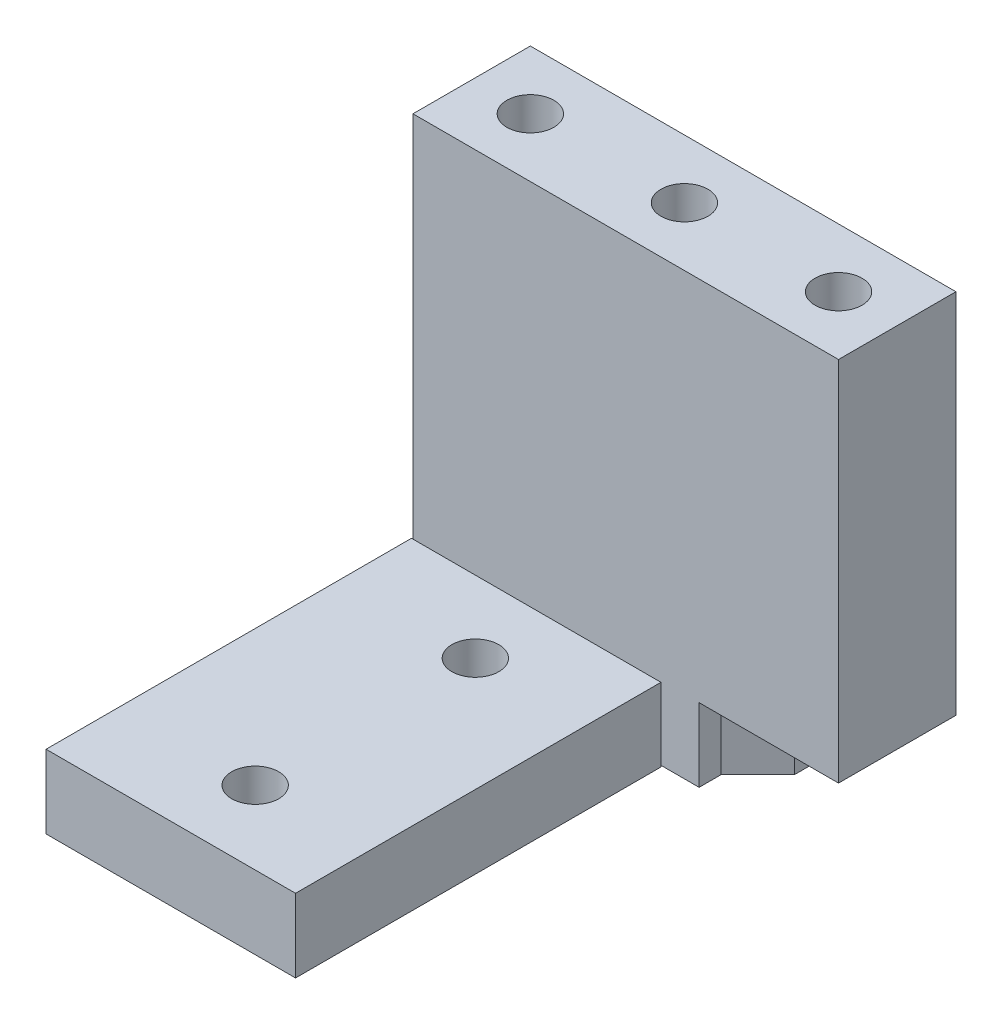
SolidWorks part; units mm, degrees
material "PLA"
ref_plane "前视基准面" through (0, 0, 0) normal (0, 0, 1) x (1, 0, 0)
ref_plane "上视基准面" through (0, 0, 0) normal (0, 1, 0) x (1, 0, 0)
ref_plane "右视基准面" through (0, 0, 0) normal (1, 0, 0) x (0, 0, -1)
sketch "草图2" plane through (0, 0, 0) normal (0, 0, 1) x (1, 0, 0)
  line L0 (-14.5, 15) -> (14.5, 15)
  line L1 (7.75, -7.75) -> (-7.75, -7.75) construction
  line L2 (7.75, -7.75) -> (7.75, 7.75) construction
  line L3 (7.75, 7.75) -> (-7.75, 7.75) construction
  line L4 (-7.75, -7.75) -> (-7.75, 7.75) construction
  line L5 (7.75, -7.75) -> (-7.75, 7.75) construction
  line L6 (7.75, 7.75) -> (-7.75, -7.75) construction
  line L7 (14.5, 15) -> (14.5, -10)
  line L9 (-14.5, -10) -> (-14.5, 15)
  line L10 (0, 0) -> (-11.4797, 0) construction
  line L11 (-7.05, -10.31) -> (-7.05, -9.46)
  line L12 (3.75, -3.69) -> (-7.05, -3.69)
  line L13 (3.75, -3.69) -> (3.75, -10.31)
  line L14 (3.75, -10.31) -> (-7.05, -10.31)
  line L15 (-7.05, -3.69) -> (-7.05, -10.31) construction
  line L16 (3.75, -3.69) -> (-7.05, -10.31) construction
  line L17 (3.75, -10.31) -> (-7.05, -3.69) construction
  line L18 (-7.05, -9.46) -> (2.9, -9.46)
  line L19 (2.9, -9.46) -> (2.9, -4.54)
  line L20 (2.9, -4.54) -> (-7.05, -4.54)
  line L21 (-7.05, -4.54) -> (-7.05, -3.69)
  line L22 (14.5, -10) -> (7.5, -10)
  line L23 (7.5, -10) -> (7.5, -15)
  line L24 (7.5, -15) -> (-14.5, -15)
  line L25 (-14.5, -15) -> (-14.5, -10)
  circle A0 centre (3.25, -10.31) radius 0.5
  circle A1 centre (3.25, -3.69) radius 0.5
  point P0 (0, 0)
  point P9 (-1.65, -7)
  point P28 (7.5, -12.5)
  dimension "D2" = 10.8
  dimension "D13" = 1
  dimension "D1" = 15.5
  dimension "D3" = 6.75
  dimension "D4" = 15
  dimension "D5" = 25
  dimension "D6" = 6.75
  dimension "D7" = 6.62
  dimension "D8" = 10
  dimension "D9" = 8
  dimension "D10" = 0.85
  dimension "D11" = 0.85
  dimension "D12" = 0.85
  dimension "D14" = 5
  dimension "D15" = 7
  dimension "D16" = 7
extrude "凸台-拉伸1" add sketch "草图2" along normal blind 8
sketch "草图3" plane through (0, 15, 0) normal (0, 1, 0) x (1, 0, 0)
  line L0 (10.5, -4) -> (14.5, -4) construction
  line L1 (14.5, -8) -> (14.5, 0) construction
  circle A0 centre (0, -4) radius 1.6
  circle A1 centre (10.5, -4) radius 1.6
  circle A2 centre (-10.5, -4) radius 1.6
  dimension "D3" = 3.2
  dimension "D1" = 10.5
  dimension "D2" = 0
  dimension "D4" = 10.5
extrude "切除-拉伸1" cut sketch "草图3" against normal through all and the other way through all
sketch "草图5" plane through (0, -15, 0) normal (0, -1, 0) x (1, 0, 0)
  line L0 (-14.5, 8) -> (-14.5, 33)
  line L1 (-14.5, 33) -> (2.5, 33)
  line L2 (2.5, 33) -> (2.5, 8)
  line L3 (2.5, 8) -> (-14.5, 8)
  dimension "D1" = 25
  dimension "D2" = 17
extrude "凸台-拉伸2" add sketch "草图5" against normal up to surface (5 mm away) up to face at (12.1, -10, 4)
sketch "草图8" plane through (0, 0, 8) normal (0, 0, 1) x (1, 0, 0)
  line L1 (-12.5, -1.6955) -> (7.5, -1.6955)
  line L2 (-12.5, -1.6955) -> (-12.5, -15)
  line L3 (-12.5, -15) -> (7.5, -15)
  line L4 (7.5, -1.6955) -> (7.5, -15)
  line L5 (-12.5, -1.6955) -> (7.5, -15) construction
  line L6 (-12.5, -15) -> (7.5, -1.6955) construction
  point P0 (-2.5, -8.3477)
  dimension "D1" = 13.3045
  dimension "D2" = 20
extrude "凸台-拉伸4" add sketch "草图8" against normal blind 1.5
sketch "草图9" plane through (0, -15, 0) normal (0, -1, 0) x (1, 0, 0)
  line L0 (7.5, 4) -> (5, 6.5)
  line L1 (7.5, 8) -> (7.5, 0) construction
  line L2 (5, 6.5) -> (5, 8)
  line L3 (7.5, 8) -> (2.5, 8) construction
  line L4 (7.5, 8) -> (7.5, 0) construction
  line L5 (14.5, 8) -> (7.5, 8) construction
  line L6 (5, 8) -> (7.5, 8)
  line M4 (7.5, 0) -> (7.5, 8)
  line M5 (7.5, 8) -> (2.5, 8)
  dimension "D1" = 45
  dimension "D2" = 4
  dimension "D3" = 2.5
extrude "切除-拉伸4" cut sketch "草图9" along direction (0, -1, 0) on the side against the normal up to surface (5 mm away) contours L2 L0 M4 M5
sketch "草图10" plane through (0, -15, 0) normal (0, -1, 0) x (1, 0, 0)
  line L0 (-14.5, 33) -> (-14.5, 0) construction
  line L1 (2.5, 33) -> (-14.5, 33) construction
  line L3 (-14.5, 8.1) -> (2.5, 8.1)
  line L4 (-14.5, 8.1) -> (-14.5, 8)
  line L5 (-14.5, 8) -> (2.5, 8)
  line L6 (2.5, 8.1) -> (2.5, 8)
  line L7 (-14.5, 8.1) -> (2.5, 8) construction
  line L8 (-14.5, 8) -> (2.5, 8.1) construction
  circle A0 centre (-5.25, 13) radius 1.6
  circle A1 centre (-5.25, 28) radius 1.6
  point P9 (-6, 8.05)
  dimension "D4" = 3.2
  dimension "D1" = 9.25
  dimension "D2" = 15
  dimension "D3" = 5
  dimension "D5" = 0.1
extrude "切除-拉伸5" cut sketch "草图10" against normal blind 10
fillet "圆角1" radius 0.2 2 edges at (2.9, -4.54, 3.25) (2.9, -9.46, 3.25)
